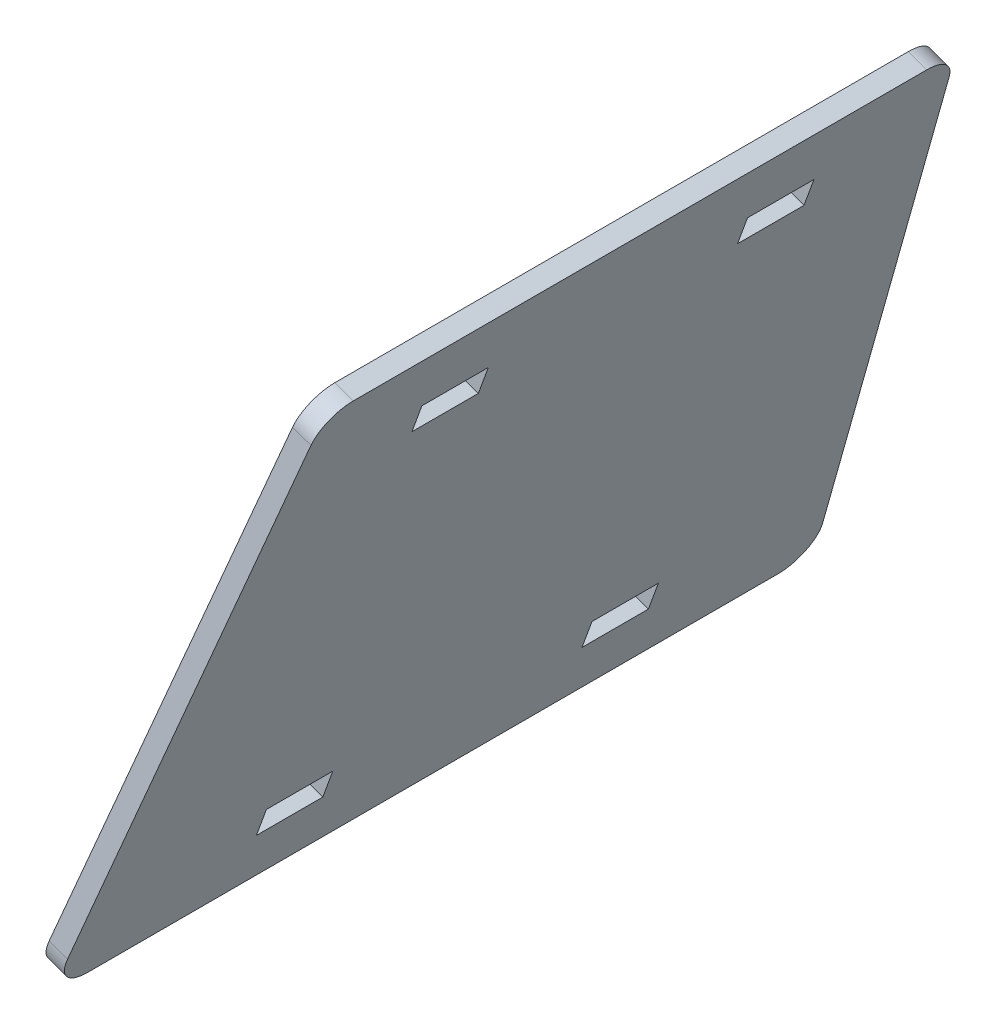
SolidWorks part; units mm, degrees
material "Acrylic (Medium-high impact)"
ref_plane "Front Plane" through (0, 0, 0) normal (0, 0, 1) x (1, 0, 0)
ref_plane "Top Plane" through (0, 0, 0) normal (0, 1, 0) x (1, 0, 0)
ref_plane "Right Plane" through (0, 0, 0) normal (1, 0, 0) x (0, 0, -1)
sketch "Sketch1" plane through (0, 0, 0) normal (0, 0, 1) x (1, 0, 0)
  line L0 (-63.8401, 220.7382) -> (-95.6594, 133.3154)
  line L1 (-95.6594, 133.3154) -> (-98.4785, 134.3414)
  line L2 (-98.4785, 134.3414) -> (-66.6592, 221.7643)
  line L3 (-66.6592, 221.7643) -> (-63.8401, 220.7382)
  line L4 (-67.2603, 211.3413) -> (-92.2392, 142.7123) construction
  line L5 (-70.4528, 211.3413) -> (-95.4318, 142.7123) construction
  dimension "D1" = 10
  dimension "D2" = 10
extrude "Boss-Extrude1" add sketch "Sketch1" along normal mid plane 116
sketch "Sketch3" plane through (-130.1352, 47.3653, 0) normal (-0.9397, 0.342, 0) x (0, 0, 1)
  line L0 (0, 0) -> (0, 273.4661) construction
  line L1 (0, 0) -> (0, 273.4661) construction
  line L2 (-58, 185.5915) -> (-58, 92.558) construction
  line L3 (58, 92.558) -> (-58, 92.558) construction
  line L4 (-44.0289, 185.5915) -> (44.0289, 185.5915)
  line L5 (-49, 181.1286) -> (-57.9711, 98.0951)
  line L6 (-53, 92.558) -> (53, 92.558)
  line L7 (49, 181.1286) -> (57.9711, 98.0951)
  line L12 (58, 185.5915) -> (-58, 185.5915) construction
  arc A0 (-44.0289, 185.5915) -> (-49, 181.1286) centre (-44.0289, 180.5915) ccw
  arc A1 (-57.9711, 98.0951) -> (-53, 92.558) centre (-53, 97.558) ccw
  arc A2 (57.9711, 98.0951) -> (53, 92.558) centre (53, 97.558) cw
  arc A3 (49, 181.1286) -> (44.0289, 185.5915) centre (44.0289, 180.5915) ccw
  point P11 (-53.8933, 185.5915)
  point P16 (58.5693, 92.558)
  point P30 (14, 92.558)
  point P45 (-14, 92.558)
  point P69 (-42, 92.558)
  point P72 (42, 92.558)
  point P75 (35, 185.5915)
  point P78 (14, 185.5915)
  point P81 (-14, 185.5915)
  point P84 (-35, 185.5915)
  dimension "D2" = 98
  dimension "D1" = 5
extrude "tab and slot contour" cut sketch "Sketch3" against normal up to next (3 mm away) flip side to cut
sketch "Sketch4" plane through (-130.1352, 47.3653, 0) normal (-0.9397, 0.342, 0) x (0, 0, 1)
  line L0 (-25, 173.4493) -> (-30, 173.4493) construction
  line L1 (-30, 175.5915) -> (-20, 175.5915) construction
  line L2 (-30, 175.5915) -> (-30, 171.307) construction
  line L3 (-30, 171.307) -> (-20, 171.307) construction
  line L4 (-20, 175.5915) -> (-20, 171.307) construction
  line L5 (-25, 175.5915) -> (-25, 171.307) construction
  line L6 (-25, 172.7724) -> (-25, 168.9687) construction
  line L7 (0, 0) -> (0, 309.9956) construction
  line L8 (-25, 105.7505) -> (-25, 101.4661) construction
  line L9 (-25, 102.9315) -> (-25, 99.0765) construction
  line L10 (-30.1, 175.6915) -> (-19.9, 175.6915)
  line L11 (-30, 105.7505) -> (-20, 105.7505) construction
  line L12 (-30, 105.7505) -> (-30, 101.4661) construction
  line L13 (-30, 101.4661) -> (-20, 101.4661) construction
  line L14 (-20, 105.7505) -> (-20, 101.4661) construction
  line L15 (-30.1, 175.6915) -> (-30.1, 171.207)
  line L16 (-30.1, 171.207) -> (-19.9, 171.207)
  line L17 (-19.9, 175.6915) -> (-19.9, 171.207)
  line L18 (-30, 103.6083) -> (-20, 103.6083) construction
  line L19 (-30.1, 105.8505) -> (-19.9, 105.8505)
  line L20 (-30.1, 105.8505) -> (-30.1, 101.3661)
  line L21 (-30.1, 101.3661) -> (-19.9, 101.3661)
  line L22 (-19.9, 105.8505) -> (-19.9, 101.3661)
  line L23 (30.1, 175.6915) -> (30.1, 171.207)
  line L24 (30.1, 175.6915) -> (19.9, 175.6915)
  line L25 (19.9, 175.6915) -> (19.9, 171.207)
  line L26 (30.1, 171.207) -> (19.9, 171.207)
  line L27 (30.1, 105.8505) -> (30.1, 101.3661)
  line L28 (30.1, 105.8505) -> (19.9, 105.8505)
  line L29 (19.9, 105.8505) -> (19.9, 101.3661)
  line L30 (30.1, 101.3661) -> (19.9, 101.3661)
  dimension "D1" = 10
  dimension "D2" = 0.1
  dimension "D3" = 0.1
extrude "mounting tab slots" cut sketch "Sketch4" against normal up to next
